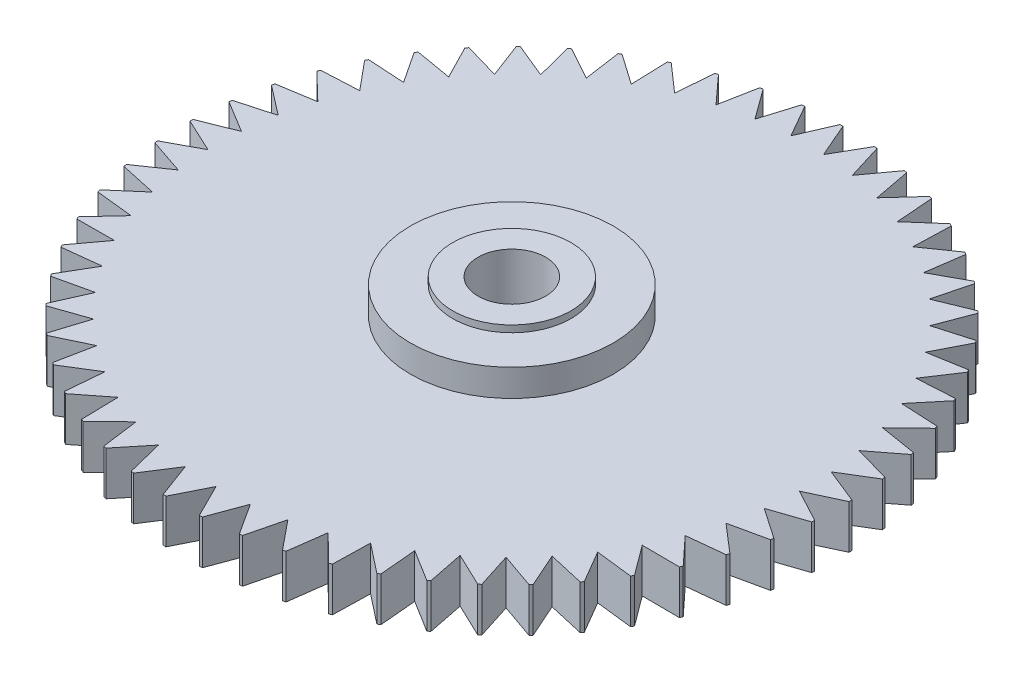
SolidWorks part; units mm, degrees
ref_plane "Plan de face" through (0, 0, 0) normal (0, 0, 1) x (1, 0, 0)
ref_plane "Plan de dessus" through (0, 0, 0) normal (0, 1, 0) x (1, 0, 0)
ref_plane "Plan de droite" through (0, 0, 0) normal (1, 0, 0) x (0, 0, -1)
sketch "Esquisse1" plane through (0, 0, 0) normal (0, 0, 1) x (1, 0, 0)
  line L0 (0, 0) -> (0, 12.6) construction
  line L1 (2, 0) -> (2, 12.6)
  line L2 (2, 12.6) -> (3.5, 12.6)
  line L3 (4.75, 6.4) -> (3.5, 6.4)
  line L4 (3.5, 6.4) -> (3.5, 12.6)
  line L9 (4.75, 6.4) -> (4.75, 0)
  line L10 (4.75, 0) -> (2, 0)
  dimension "D1" = 4
  dimension "D2" = 9.5
  dimension "D3" = 6.4
  dimension "D4" = 12.6
  dimension "D5" = 7
revolve "Révolution1" add sketch "Esquisse1" angle 360 about L0
sketch "Esquisse2" plane through (0, 0, 0) normal (0, 0, 1) x (1, 0, 0)
  line L0 (0, 12.6) -> (0, 0) construction
  line L1 (2, 12.6) -> (-2, 12.6) construction
  line L5 (3.5, 6.4) -> (6, 6.4)
  line L6 (6, 6.4) -> (6, 8)
  line L7 (6, 8) -> (19.5, 8)
  line L8 (19.5, 8) -> (19.5, 10.6)
  line L9 (19.5, 10.6) -> (6, 10.6)
  line L10 (6, 10.6) -> (6, 12.2)
  line L11 (6, 12.2) -> (3.5, 12.2)
  line L12 (3.5, 12.2) -> (3.5, 6.4)
  dimension "D1" = 2.6
  dimension "D2" = 5.8
  dimension "D3" = 12
  dimension "D4" = 39
revolve "Révolution2" add sketch "Esquisse2" angle 360 about L0
sketch "Esquisse3" plane through (0, 8, 0) normal (0, -1, 0) x (1, 0, 0)
  line L0 (-1, 19.5) -> (1, 19.5)
  line L1 (1, 19.5) -> (0, 17.5)
  line L2 (0, 17.5) -> (-1, 19.5)
  circle A0 centre (0, 0) radius 19.5 construction
  point P2 (0, 19.5)
  dimension "D1" = 2
  dimension "D2" = 2
extrude "Enlèv. mat.-Extru.1" cut sketch "Esquisse3" against normal through all
pattern_circular "Répétition circulaire1" count 57 over 360 about axis through (0, 0, 0) along (0, 1, 0) of "Enlèv. mat.-Extru.1"
